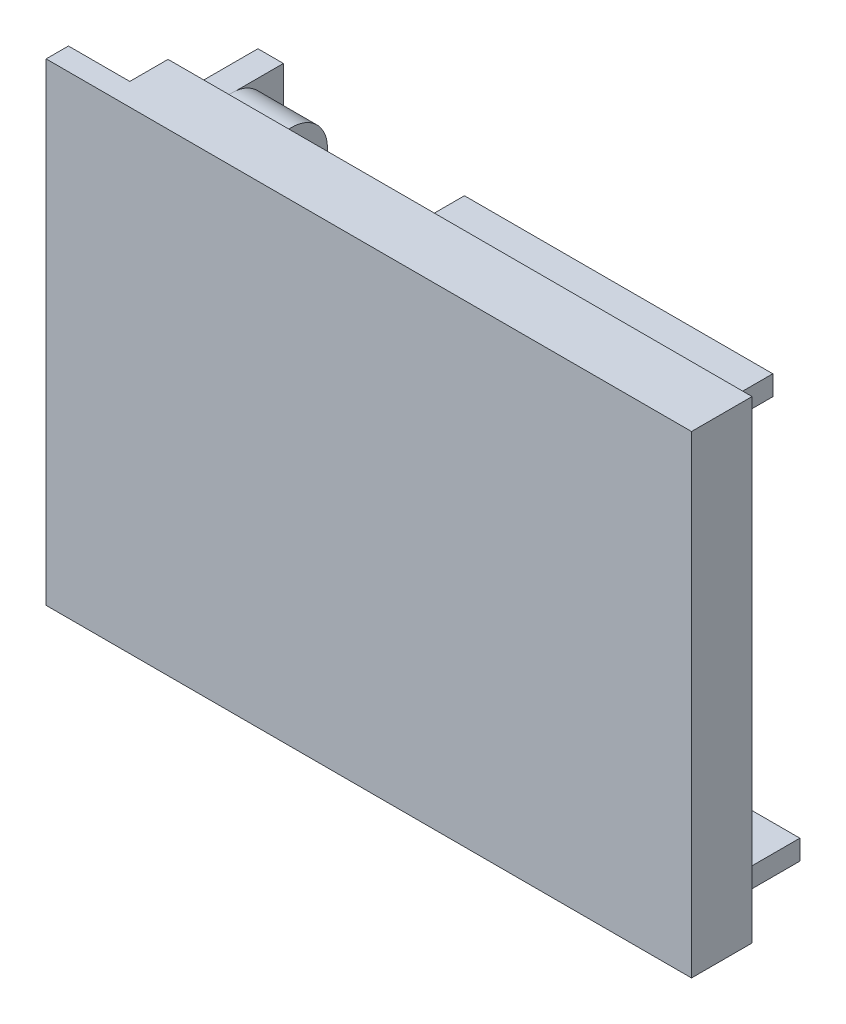
SolidWorks part; units mm, degrees
ref_plane "Front Plane" through (0, 0, 0) normal (0, 0, 1) x (1, 0, 0)
ref_plane "Top Plane" through (0, 0, 0) normal (0, 1, 0) x (1, 0, 0)
ref_plane "Right Plane" through (0, 0, 0) normal (1, 0, 0) x (0, 0, -1)
sketch "Sketch1" plane through (0, 0, 0) normal (0, 0, 1) x (1, 0, 0)
  line L1 (-40.5, -29.7) -> (40.5, -29.7)
  line L2 (-40.5, -29.7) -> (-40.5, 29.7)
  line L3 (-40.5, 29.7) -> (40.5, 29.7)
  line L4 (40.5, -29.7) -> (40.5, 29.7)
  line L5 (-40.5, -29.7) -> (40.5, 29.7) construction
  line L6 (-40.5, 29.7) -> (40.5, -29.7) construction
  point P0 (0, 0)
  dimension "D1" = 81
  dimension "D2" = 59.4
extrude "Carrier / Base" add sketch "Sketch1" along normal blind 7.6
sketch "Sketch2" plane through (0, 0, 0) normal (0, 0, -1) x (-1, 0, 0)
  line L0 (40.5, -29.7) -> (-40.5, -29.7) construction
  line L1 (40.5, 29.7) -> (32.8, 29.7)
  line L2 (40.5, 29.7) -> (40.5, -29.7)
  line L3 (40.5, -29.7) -> (32.8, -29.7)
  line L4 (32.8, 29.7) -> (32.8, -29.7)
  dimension "D1" = 7.7
extrude "Cut-Extrude1" cut sketch "Sketch2" against normal blind 4.8
sketch "Sketch3" plane through (0, 0, 0) normal (0, 0, -1) x (-1, 0, 0)
  line L7 (-34.8, 25.177) -> (3.9, 25.177)
  line L8 (-34.8, 25.177) -> (-34.8, 22.677)
  line L9 (-34.8, 22.677) -> (3.9, 22.677)
  line L10 (3.9, 25.177) -> (3.9, 22.677)
  dimension "D1" = 38.7
  dimension "D2" = 2.5
extrude "Analog / Power Bank" add sketch "Sketch3" along normal blind 8.3
sketch "Sketch4" plane through (0, 0, 0) normal (0, 0, -1) x (-1, 0, 0)
  line L5 (-38.2, -26.1) -> (-1, -26.1)
  line L6 (-38.2, -26.1) -> (-38.2, -23.6)
  line L7 (-38.2, -23.6) -> (-1, -23.6)
  line L8 (-1, -26.1) -> (-1, -23.6)
  dimension "D3" = 37.2
  dimension "D4" = 2.5
extrude "Digital Bank" add sketch "Sketch4" along normal blind 8.3
sketch "Sketch5" plane through (0, 0, 0) normal (0, 0, -1) x (-1, 0, 0)
  line L6 (32.8196, 25.1946) -> (29.6196, 25.1946)
  line L7 (32.8196, 25.1946) -> (32.8196, 16.3946)
  line L8 (32.8196, 16.3946) -> (29.6196, 16.3946)
  line L9 (29.6196, 25.1946) -> (29.6196, 16.3946)
  dimension "D1" = 3.2
  dimension "D2" = 8.8
extrude "5V Input" add sketch "Sketch5" along normal blind 11.3
sketch "Sketch7" plane through (-29.6196, 0, 0) normal (1, 0, 0) x (0, 0, -1)
  circle A0 centre (4.8278, 20.7309) radius 4.5
extrude "Boss-Extrude6" add sketch "Sketch7" along normal blind 7.5
sketch "Sketch8" plane through (-32.8196, 0, 0) normal (-1, 0, 0) x (0, 0, 1)
  circle A0 centre (-5.2416, 20.9853) radius 3.0193
extrude "Cut-Extrude2" cut sketch "Sketch8" against normal blind 5
sketch "Sketch9" plane through (0, 0, 0) normal (0, 0, -1) x (-1, 0, 0)
  line L5 (32.8, -17.6) -> (26.4, -17.6)
  line L6 (32.8, -17.6) -> (32.8, -8.7)
  line L7 (32.8, -8.7) -> (26.4, -8.7)
  line L8 (26.4, -17.6) -> (26.4, -8.7)
  dimension "D2" = 8.9
  dimension "D3" = 6.4
extrude "USB-C" add sketch "Sketch9" along normal blind 3.4
fillet "Fillet3" radius 0.5 4 edges at (-29.6, -17.6, -3.4) (-26.4, -13.15, -3.4) (-29.6, -8.7, -3.4) (-32.8, -13.15, -3.4)
sketch "Sketch10" plane through (-32.8, 0, 0) normal (-1, 0, 0) x (0, 0, 1)
  line L0 (-1.2291, -16.6314) -> (-1.2291, -9.7896) construction
  line L1 (-1.9282, -16.6314) -> (-1.9282, -9.7896)
  line L2 (-0.5299, -16.6314) -> (-0.5299, -9.7896)
  arc A0 (-1.9282, -16.6314) -> (-0.5299, -16.6314) centre (-1.2291, -16.6314) ccw
  arc A1 (-0.5299, -9.7896) -> (-1.9282, -9.7896) centre (-1.2291, -9.7896) ccw
  point P2 (-1.2291, -13.2105)
extrude "Cut-Extrude3" cut sketch "Sketch10" against normal blind 5.8
sketch "Sketch11" plane through (0, 0, 0) normal (0, 0, -1) x (-1, 0, 0)
  line L1 (31.0727, -28.1422) -> (24.5727, -28.1422)
  line L2 (31.0727, -28.1422) -> (31.0727, -21.6422)
  line L3 (31.0727, -21.6422) -> (24.5727, -21.6422)
  line L4 (24.5727, -28.1422) -> (24.5727, -21.6422)
  dimension "D1" = 6.5
  dimension "D2" = 6.5
extrude "Boss-Extrude12" add sketch "Sketch11" along normal blind 1.75
sketch "Sketch12" plane through (0, 0, -1.75) normal (0, 0, -1) x (-1, 0, 0)
  circle A0 centre (27.8753, -25.1721) radius 1.6975
extrude "Reset" add sketch "Sketch12" along normal blind 1.75
